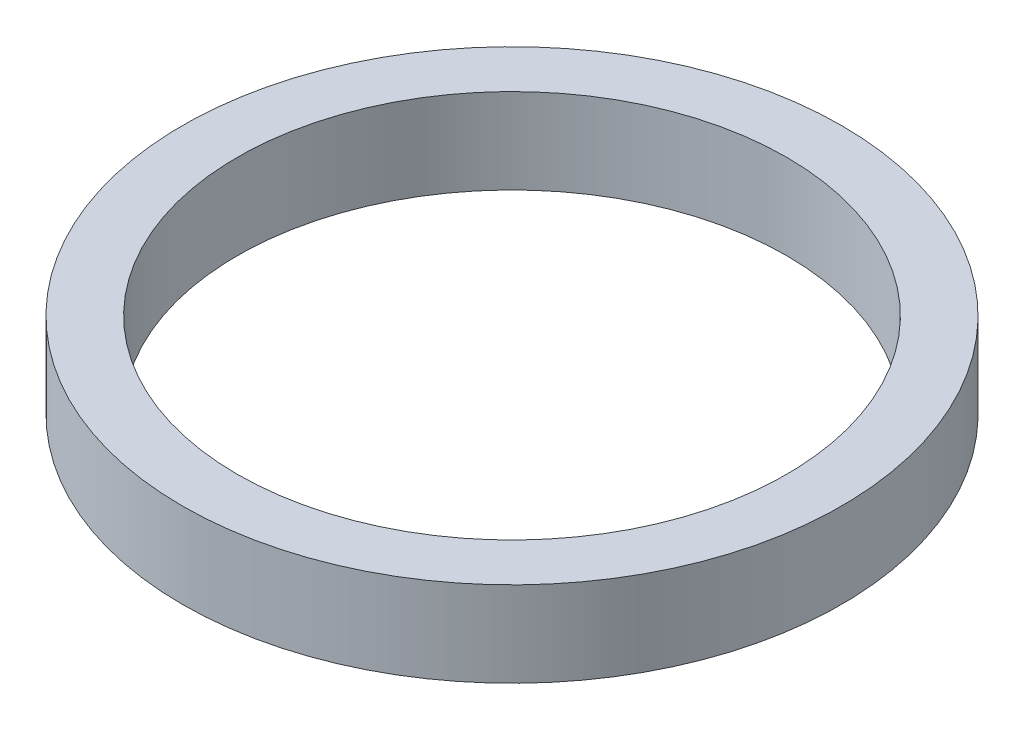
SolidWorks part; units mm, degrees
ref_plane "Front Plane" through (0, 0, 0) normal (0, 0, 1) x (1, 0, 0)
ref_plane "Top Plane" through (0, 0, 0) normal (0, 1, 0) x (1, 0, 0)
ref_plane "Right Plane" through (0, 0, 0) normal (1, 0, 0) x (0, 0, -1)
sketch "Sketch1" plane through (0, 0, 0) normal (0, 1, 0) x (1, 0, 0)
  circle A0 centre (0, 0) radius 9.525
  circle A1 centre (0, 0) radius 7.9375
  dimension "D1" = 15.875
  dimension "D2" = 19.05
extrude "Boss-Extrude1" add sketch "Sketch1" along normal blind 2.4638
